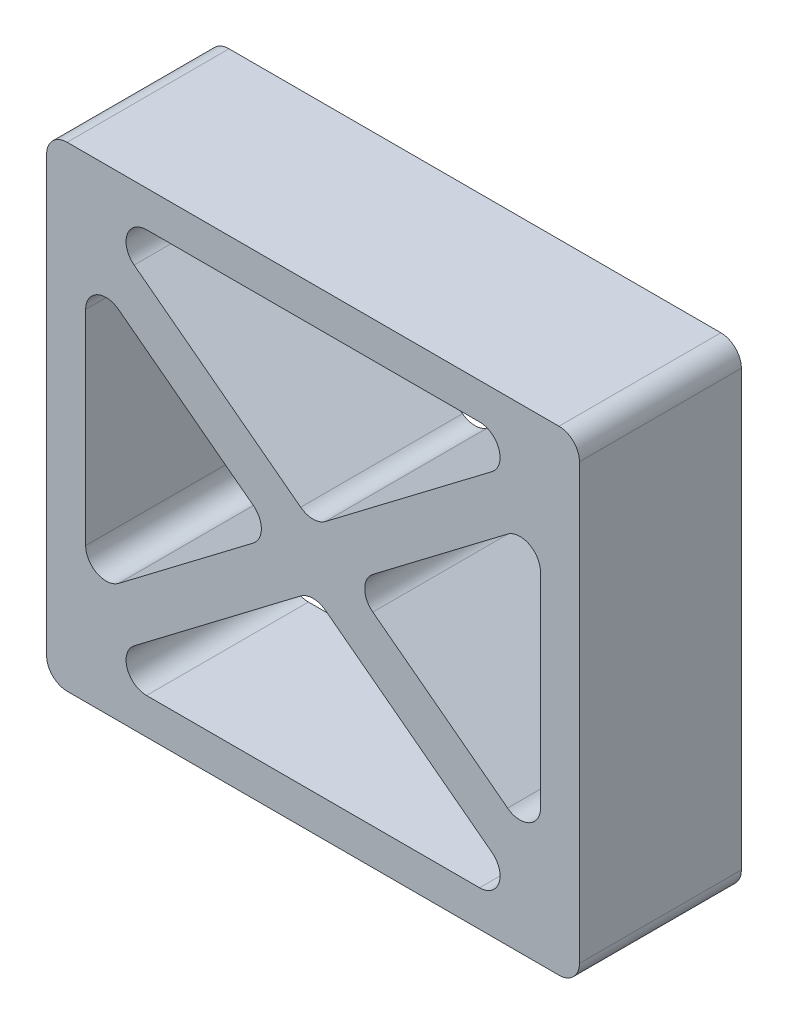
SolidWorks part; units mm, degrees
material "6061-O (SS)"
ref_plane "Alzado" through (0, 0, 0) normal (0, 0, 1) x (1, 0, 0)
ref_plane "Planta" through (0, 0, 0) normal (0, 1, 0) x (1, 0, 0)
ref_plane "Vista lateral" through (0, 0, 0) normal (1, 0, 0) x (0, 0, -1)
sketch "Croquis1" plane through (0, 0, 0) normal (0, 0, 1) x (1, 0, 0)
  line L1 (-54.4164, 45.1223) -> (75.5836, 45.1223)
  line L2 (-54.4164, 45.1223) -> (-54.4164, -70.8777)
  line L3 (-54.4164, -70.8777) -> (75.5836, -70.8777)
  line L4 (75.5836, 45.1223) -> (75.5836, -70.8777)
  dimension "D1" = 130
  dimension "D2" = 116
extrude "Saliente-Extruir1" add sketch "Croquis1" along normal blind 39.5
sketch "Croquis2" plane through (0, 0, 39.5) normal (0, 0, 1) x (1, 0, 0)
  line L0 (-44.9018, 36.3313) -> (66.0689, 36.3313)
  line L1 (10.5836, 45.1223) -> (10.5836, 36.3313) construction
  line L2 (-54.4164, -12.8777) -> (-44.9018, -12.8777) construction
  line L3 (-54.4164, 45.1223) -> (-54.4164, -70.8777) construction
  line L4 (-44.9018, -12.8777) -> (1.2484, -12.8777) construction
  line L6 (66.0689, 36.3313) -> (10.5836, -5.7908)
  line L7 (10.5836, -5.7908) -> (-44.9018, 36.3313)
  line L8 (-44.9018, 22.1575) -> (-44.9018, -47.9129)
  line L9 (-44.9018, -47.9129) -> (1.2484, -12.8777)
  line L10 (1.2484, -12.8777) -> (-44.9018, 22.1575)
  line L11 (19.9188, -12.8777) -> (66.0689, 22.1575)
  line L12 (66.0689, 22.1575) -> (66.0689, -47.9129)
  line L13 (66.0689, -47.9129) -> (19.9188, -12.8777)
  line L14 (-44.9018, -62.0866) -> (10.5836, -19.9646)
  line L15 (10.5836, -19.9646) -> (66.0689, -62.0866)
  line L16 (66.0689, -62.0866) -> (-44.9018, -62.0866)
  line L17 (75.5836, 45.1223) -> (-54.4164, 45.1223) construction
  line L18 (10.5836, 36.3313) -> (10.5836, -5.7908) construction
  line L19 (10.5836, -19.9646) -> (10.5836, -62.0866) construction
  line L20 (10.5836, -62.0866) -> (10.5836, -70.8777) construction
  line L21 (-54.4164, -70.8777) -> (75.5836, -70.8777) construction
  line L22 (19.9188, -12.8777) -> (66.0689, -12.8777) construction
  line L23 (66.0689, -12.8777) -> (75.5836, -12.8777) construction
  line L24 (75.5836, -70.8777) -> (75.5836, 45.1223) construction
extrude "Cortar-Extruir1" cut sketch "Croquis2" against normal blind 39.5
fillet "Redondeo1" radius 5 16 edges at (66.0689, 22.1575, 19.75) (19.9188, -12.8777, 19.75) (66.0689, -47.9129, 19.75) (66.0689, -62.0866, 19.75) (-44.9018, -62.0866, 19.75) (10.5836, -19.9646, 19.75) (1.2484, -12.8777, 19.75) (-44.9018, -47.9129, 19.75) (10.5836, -5.7908, 19.75) (-44.9018, 22.1575, 19.75) (75.5836, 45.1223, 19.75) (75.5836, -70.8777, 19.75) (-54.4164, -70.8777, 19.75) (-54.4164, 45.1223, 19.75) (66.0689, 36.3313, 19.75) (-44.9018, 36.3313, 19.75)
